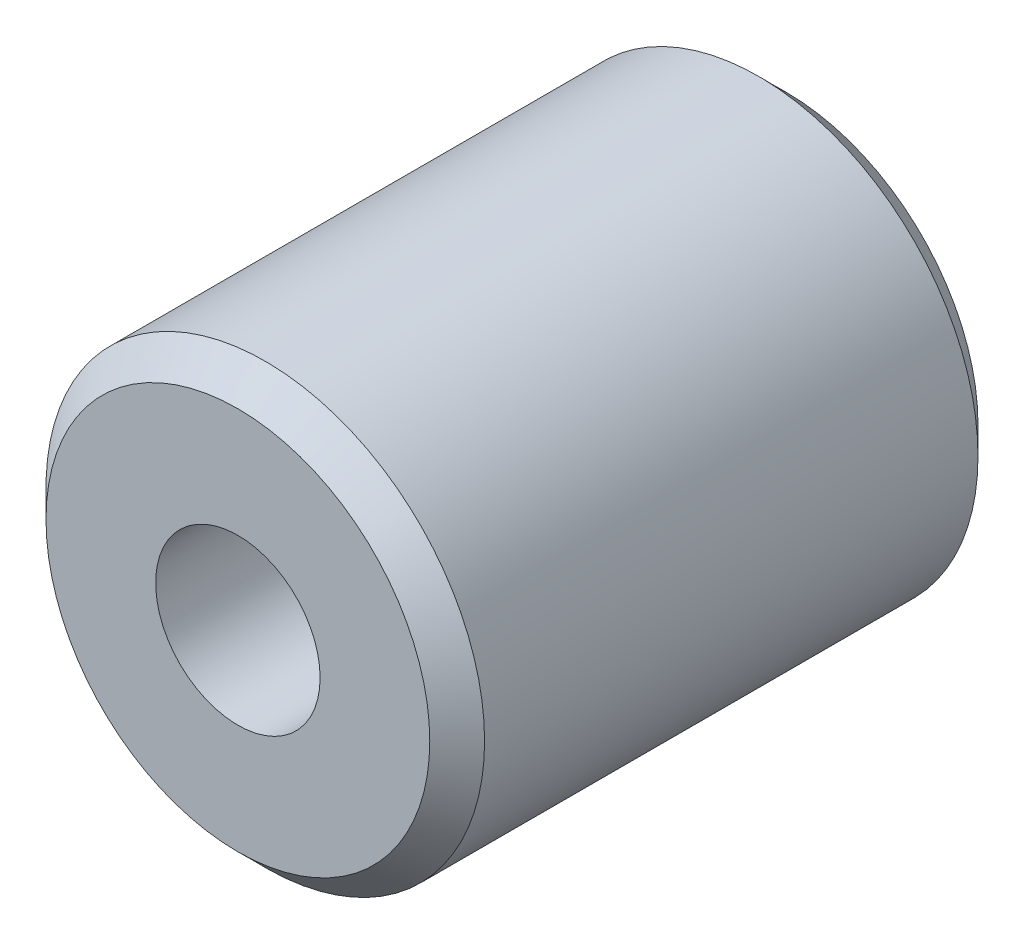
SolidWorks part; units mm, degrees
ref_plane "Plan1" through (0, 0, 0) normal (0, 0, 1) x (1, 0, 0)
ref_plane "Plan2" through (0, 0, 0) normal (0, 1, 0) x (1, 0, 0)
ref_plane "Plan3" through (0, 0, 0) normal (1, 0, 0) x (0, 0, -1)
sketch "Esquisse1" plane through (0, 0, 0) normal (0, 0, 1) x (1, 0, 0)
  circle A0 centre (0, 0) radius 4
  dimension "D1" = 8
extrude "Base-Extrusion" add sketch "Esquisse1" along normal blind 10
chamfer "Chanfrein1" distance 0.5 angle 45
sketch "Esquisse2" plane through (0, 0, 10) normal (0, 0, 1) x (1, 0, 0)
  circle A0 centre (0, 0) radius 1.5
  dimension "D1" = 3
extrude "Enlèv. mat.-Extru.1" cut sketch "Esquisse2" against normal through all
sketch "Esquisse3" plane through (0, 0, 0) normal (0, 0, -1) x (-1, 0, 0)
  line L2 (1.5811, 2.7386) -> (-1.5811, 2.7386)
  line L3 (1.5811, 2.7386) -> (3.1623, 0)
  line L4 (3.1623, 0) -> (1.5811, -2.7386)
  line L5 (1.5811, -2.7386) -> (-1.5811, -2.7386)
  line L6 (-1.5811, -2.7386) -> (-3.1623, 0)
  line L7 (-3.1623, 0) -> (-1.5811, 2.7386)
extrude "Enlèv. mat.-Extru.2" cut sketch "Esquisse3" against normal blind 6
